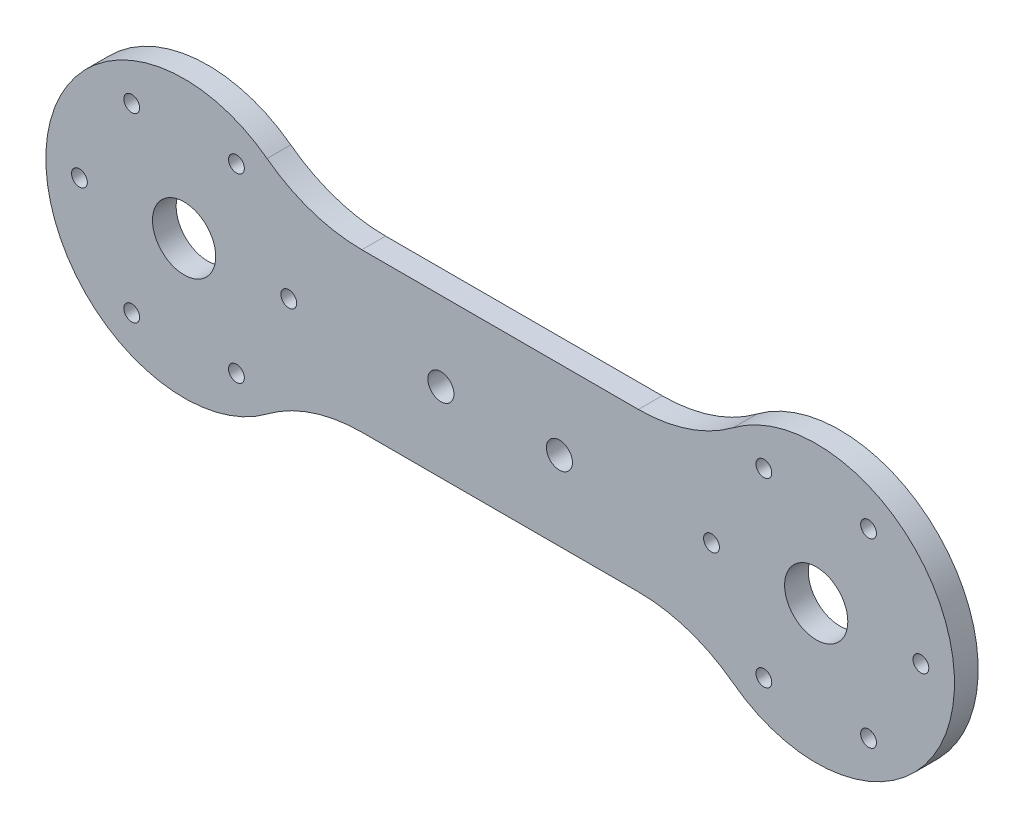
SolidWorks part; units mm, degrees
material "ABS"
ref_plane "Plano frontal" through (0, 0, 0) normal (0, 0, 1) x (1, 0, 0)
ref_plane "Plano superior" through (0, 0, 0) normal (0, 1, 0) x (1, 0, 0)
ref_plane "Plano direito" through (0, 0, 0) normal (1, 0, 0) x (0, 0, -1)
sketch "Esboço1" plane through (0, 0, 0) normal (0, 0, 1) x (1, 0, 0)
  line L0 (14.3614, -10) -> (65.6386, -10)
  line L1 (0, 0) -> (80, 0) construction
  line L2 (14.3614, 10) -> (65.6386, 10)
  line L3 (0, 10) -> (80, 10) construction
  line L4 (0, -10) -> (80, -10) construction
  line L5 (40, 10) -> (40, -10) construction
  line L7 (0, 0) -> (80, 0) construction
  circle A0 centre (0, 0) radius 4
  circle A1 centre (-13.25, 0) radius 1
  circle A2 centre (0, 0) radius 4
  arc A3 (14.3614, 10) -> (14.3614, -10) centre (0, 0) ccw
  circle A4 centre (-6.625, 11.4748) radius 1
  circle A5 centre (0, 0) radius 4
  circle A6 centre (86.625, -11.4748) radius 1
  circle A7 centre (6.625, 11.4748) radius 1
  circle A8 centre (0, 0) radius 4
  circle A9 centre (80, 0) radius 4
  circle A10 centre (13.25, 0) radius 1
  circle A11 centre (0, 0) radius 4
  circle A12 centre (6.625, -11.4748) radius 1
  circle A13 centre (0, 0) radius 4
  circle A14 centre (-6.625, -11.4748) radius 1
  circle A15 centre (73.375, -11.4748) radius 1
  circle A16 centre (80, 0) radius 4
  circle A17 centre (66.75, 0) radius 1
  circle A18 centre (80, 0) radius 4
  circle A19 centre (73.375, 11.4748) radius 1
  circle A20 centre (80, 0) radius 4
  circle A21 centre (86.625, 11.4748) radius 1
  arc A22 (65.6386, 10) -> (65.6386, -10) centre (80, 0) cw
  circle A23 centre (80, 0) radius 4
  circle A24 centre (93.25, 0) radius 1
  circle A25 centre (80, 0) radius 4
  circle A26 centre (32.5, 0) radius 1.65
  circle A27 centre (47.5, 0) radius 1.65
  point P14 (40, 0)
  point P32 (0, 0)
  dimension "D1" = 8
  dimension "D3" = 2
  dimension "D4" = 13.25
  dimension "D6" = 6
  dimension "D8" = 35
  dimension "D9" = 3.3
  dimension "D2" = 10
  dimension "D5" = 10
  dimension "D7" = 40
  dimension "D10" = 15
  dimension "D11" = 32.5
extrude "Ressalto-extrusão1" add sketch "Esboço1" along normal blind 3 contours A22 L2 A3 L0 A21 A17 A9 A7 A0 A1 A4 A6 A10 A12 A14 A15 A19 A24
fillet "Filete1" radius 20 4 edges at (14.3614, -10, 1.5) (65.6386, -10, 1.5) (65.6386, 10, 1.5) (14.3614, 10, 1.5)
